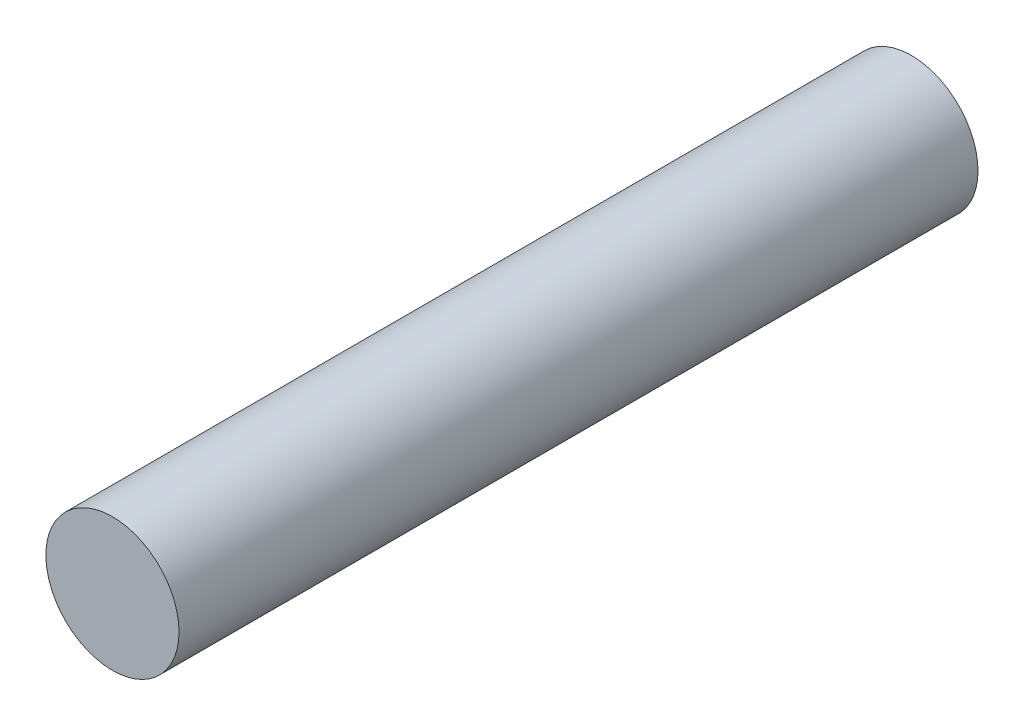
SolidWorks part; units mm, degrees
ref_plane "前视基准面" through (0, 0, 0) normal (0, 0, 1) x (1, 0, 0)
ref_plane "上视基准面" through (0, 0, 0) normal (0, 1, 0) x (1, 0, 0)
ref_plane "右视基准面" through (0, 0, 0) normal (1, 0, 0) x (0, 0, -1)
sketch "草图1" plane through (0, 0, 0) normal (0, 0, 1) x (1, 0, 0)
  circle A0 centre (0, 0) radius 2.5
  dimension "D1" = 5
extrude "凸台-拉伸1" add sketch "草图1" along normal blind 30
